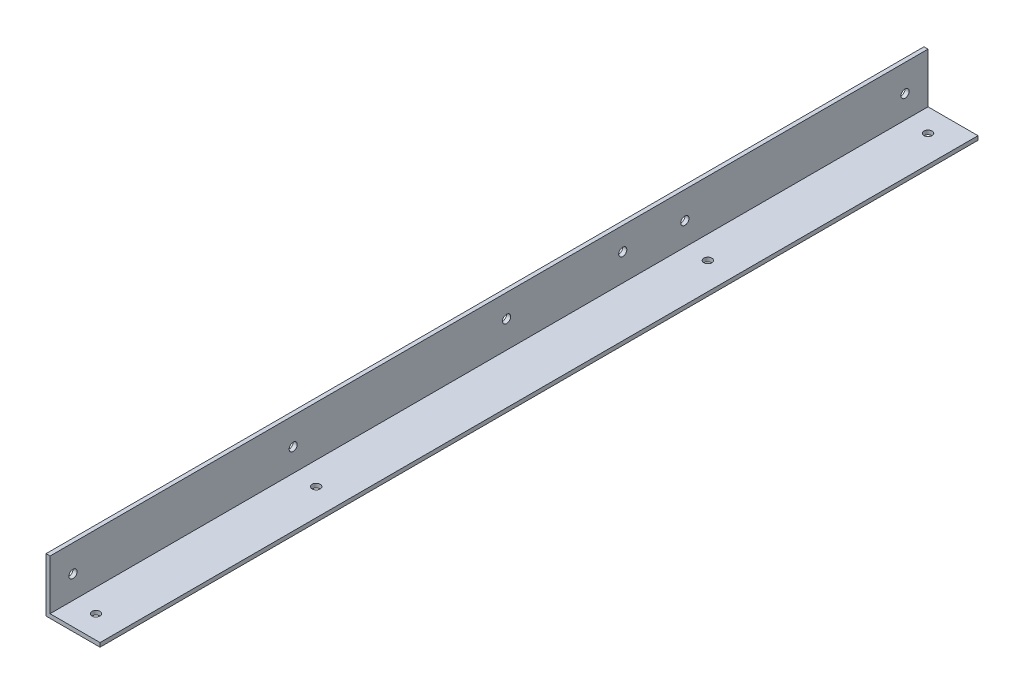
SolidWorks part; units mm, degrees
ref_plane "Plan de face" through (0, 0, 0) normal (0, 0, 1) x (1, 0, 0)
ref_plane "Plan de dessus" through (0, 0, 0) normal (0, 1, 0) x (1, 0, 0)
ref_plane "Plan de droite" through (0, 0, 0) normal (1, 0, 0) x (0, 0, -1)
sketch "Esquisse1" plane through (0, 0, 0) normal (0, 0, 1) x (1, 0, 0)
  line L0 (-17.4317, 4.7734) -> (-17.4317, -15.2266)
  line L1 (-17.4317, -15.2266) -> (2.5683, -15.2266)
  line L2 (2.5683, -15.2266) -> (2.5683, -13.7266)
  line L3 (2.5683, -13.7266) -> (-15.9317, -13.7266)
  line L4 (-15.9317, -13.7266) -> (-15.9317, 4.7734)
  line L5 (-15.9317, 4.7734) -> (-17.4317, 4.7734)
  dimension "D1" = 1.5
  dimension "D2" = 1.5
  dimension "D3" = 20
  dimension "D4" = 20
extrude "Extrusion1" add sketch "Esquisse1" along normal blind 325
sketch "Esquisse2" plane through (0, -13.7266, 0) normal (0, 1, 0) x (-1, 0, 0)
  line L0 (-2.5683, 325) -> (-2.5683, 0) construction
  line L1 (-2.5683, 325) -> (15.9317, 325) construction
  line L2 (-2.5683, 0) -> (15.9317, 0) construction
  circle A0 centre (7.4317, 8.5) radius 1.5
  circle A1 centre (7.4317, 316.5) radius 1.5
  circle A2 centre (7.4317, 235) radius 1.5
  circle A3 centre (7.4317, 90) radius 1.5
  dimension "D1" = 8.5
  dimension "D5" = 90
  dimension "D2" = 8.5
  dimension "D3" = 10
  dimension "D4" = 10
  dimension "D6" = 90
  dimension "D7" = 10
  dimension "D8" = 10
extrude "Extrusion2" cut sketch "Esquisse2" against normal blind 300
sketch "Esquisse3" plane through (-15.9317, 0, 0) normal (1, 0, 0) x (0, 0, -1)
  line L0 (-316.5, -5.2266) -> (-8.5, -5.2266) construction
  line L1 (-325, -13.7266) -> (-325, 4.7734) construction
  line L2 (0, -13.7266) -> (0, 4.7734) construction
  line L3 (-325, 4.7734) -> (0, 4.7734) construction
  line L4 (-325, 4.7734) -> (0, 4.7734) construction
  circle A0 centre (-316.5, -5.2266) radius 1.5
  circle A1 centre (-8.5, -5.2266) radius 1.5
  circle A2 centre (-235, -5.2266) radius 1.5
  circle A3 centre (-90, -5.2266) radius 1.5
  circle A4 centre (-113, -3.7266) radius 1.5
  circle A5 centre (-156, -3.7266) radius 1.5
  point P14 (-325, -4.4766)
  dimension "D1" = 8.5
  dimension "D4" = 90
  dimension "D6" = 23
  dimension "D2" = 8.5
  dimension "D3" = 10
  dimension "D5" = 90
  dimension "D7" = 43
  dimension "D8" = 8.5
  dimension "D9" = 8.5
extrude "Extrusion3" cut sketch "Esquisse3" against normal blind 300
